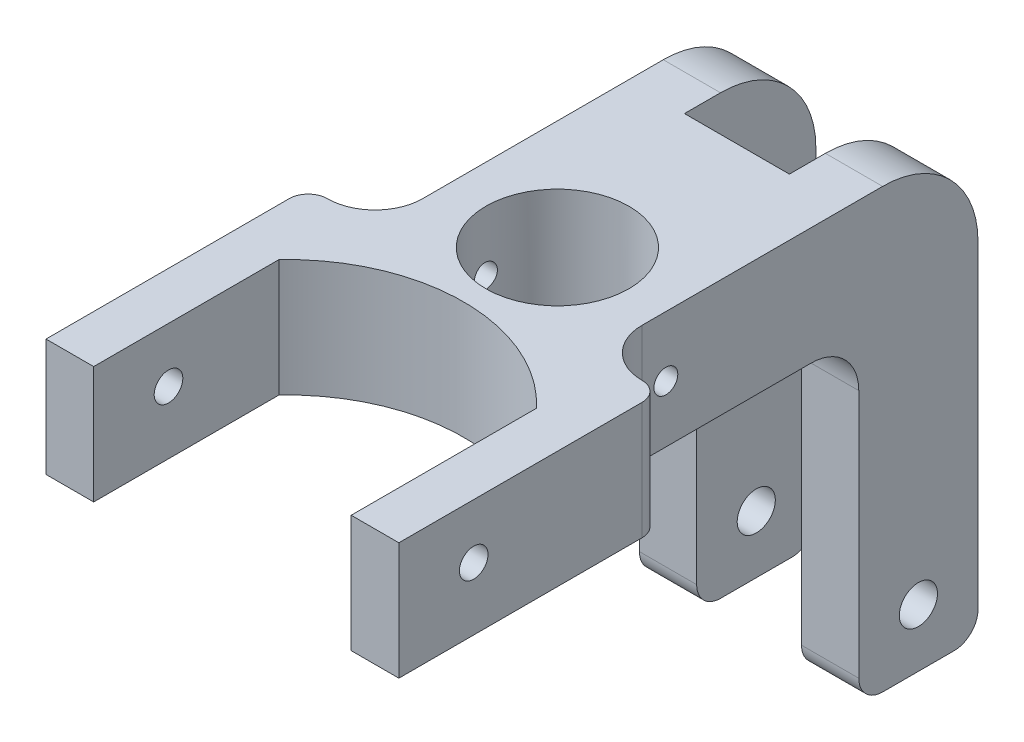
SolidWorks part; units mm, degrees
ref_plane "Спереди" through (0, 0, 0) normal (0, 0, 1) x (1, 0, 0)
ref_plane "Сверху" through (0, 0, 0) normal (0, 1, 0) x (1, 0, 0)
ref_plane "Справа" through (0, 0, 0) normal (1, 0, 0) x (0, 0, -1)
sketch "Эскиз1" plane through (0, 0, 0) normal (1, 0, 0) x (0, 0, -1)
  line L0 (3.6837, 0) -> (3.6837, -24.5969)
  line L1 (3.6837, -24.5969) -> (49.1322, -24.5969)
  line L3 (3.6837, 0) -> (64.1322, 0)
  line L7 (59.1322, -34.5969) -> (59.1321, -86.8316)
  line L8 (64.1321, -91.8316) -> (79.1322, -91.8316)
  line L9 (84.1322, -86.8316) -> (84.1322, -20)
  arc A0 (84.1322, -20) -> (64.1322, 0) centre (64.1322, -20) ccw
  arc A1 (59.1322, -34.5969) -> (49.1322, -24.5969) centre (49.1322, -34.5969) ccw
  arc A2 (64.1321, -91.8316) -> (59.1321, -86.8316) centre (64.1321, -86.8316) cw
  arc A3 (84.1322, -86.8316) -> (79.1322, -91.8316) centre (79.1322, -86.8316) cw
  dimension "D1" = 20
  dimension "D2" = 10
  dimension "D3" = 5
  dimension "D4" = 91.8316
extrude "Вытянуть1" add sketch "Эскиз1" along normal blind 46 from offset 3 offset against normal yes
sketch "Эскиз2" plane through (0, 0, 0) normal (0, 1, 0) x (1, 0, 0)
  line L0 (20, 84.1322) -> (20, 104.5676) construction
  line L1 (9, 97.5814) -> (9, 56.5775)
  line L3 (31, 97.5814) -> (31, 56.5775)
  line L5 (9, 97.5814) -> (31, 97.5814)
  line L6 (31, 56.5775) -> (9, 56.5775)
  circle A0 centre (20, 18.9317) radius 15
  dimension "D1" = 30
  dimension "D2" = 11
extrude "Вытянуть2" cut sketch "Эскиз2" against normal mid plane 240
sketch "Эскиз3" plane through (0, 0, 0) normal (1, 0, 0) x (0, 0, -1)
  line L0 (5.675, 15.3538) -> (5.675, 28.3206) construction
  line L3 (31.675, 29.692) -> (31.675, 13.6083) construction
  line L6 (18.675, 32.1857) -> (18.675, 12.9849) construction
  circle A0 centre (71.6321, -79.6954) radius 4
  circle A1 centre (18.675, -12.6282) radius 2.5
  dimension "D2" = 13
extrude "Вырез-Вытянуть1" cut sketch "Эскиз3" against normal mid plane 110
sketch "Эскиз4" plane through (0, 0, -3.6837) normal (0, 0, 1) x (1, 0, 0)
  line L0 (57.0034, -24.5969) -> (-16.9966, -24.5969)
  line L1 (57.0034, -24.5969) -> (57.0034, 0)
  line L2 (57.0034, 0) -> (-16.9966, 0)
  line L3 (-16.9966, 0) -> (-16.9966, -24.5969)
  line L4 (47.0034, -21.462) -> (47.0034, -1.462) construction
  line L6 (-6.9966, -1.462) -> (-6.9966, -21.462) construction
  dimension "D1" = 10
  dimension "D2" = 10
extrude "Вытянуть3" add sketch "Эскиз4" along normal blind 55
sketch "Эскиз6" plane through (0, 0, 0) normal (0, 1, 0) x (1, 0, 0)
  line L0 (47.0034, -53.7128) -> (47.0034, -12.467)
  line L2 (-6.9966, -12.467) -> (-6.9966, -53.7128)
  line L3 (-6.9966, -53.7128) -> (47.0034, -53.7128)
  arc A0 (47.0034, -12.467) -> (-6.9966, -12.467) centre (20.0034, -37.7653) ccw
extrude "Вырез-Вытянуть2" cut sketch "Эскиз6" along normal mid plane 100
fillet "Скругление2" radius 4 2 edges at (57.0034, -12.2984, -3.6837) (-16.9966, -12.2984, -3.6837)
sketch "Эскиз7" plane through (57.0034, 0, 0) normal (1, 0, 0) x (0, 0, -1)
  circle A0 centre (-35.6235, -11.4606) radius 3
extrude "Вырез-Вытянуть3" cut sketch "Эскиз7" against normal mid plane 180
fillet "Скругление3" radius 10 2 edges
sketch "Эскиз8" plane through (0, 0, 0) normal (0, 0, 1) x (1, 0, 0)
  line L0 (-16.9966, 0) -> (57.0034, -72.4866) construction
  line L1 (-16.9966, 0) -> (57.0034, 0) construction
  line L2 (-16.9966, 0) -> (-16.9966, -72.4866) construction
  line L3 (-16.9966, -72.4866) -> (57.0034, -72.4866) construction
  line L4 (57.0034, 0) -> (57.0034, -72.4866) construction
  line L5 (57.0034, 0) -> (-16.9966, -72.4866) construction
  circle A0 centre (20.0034, -36.2433) radius 50
